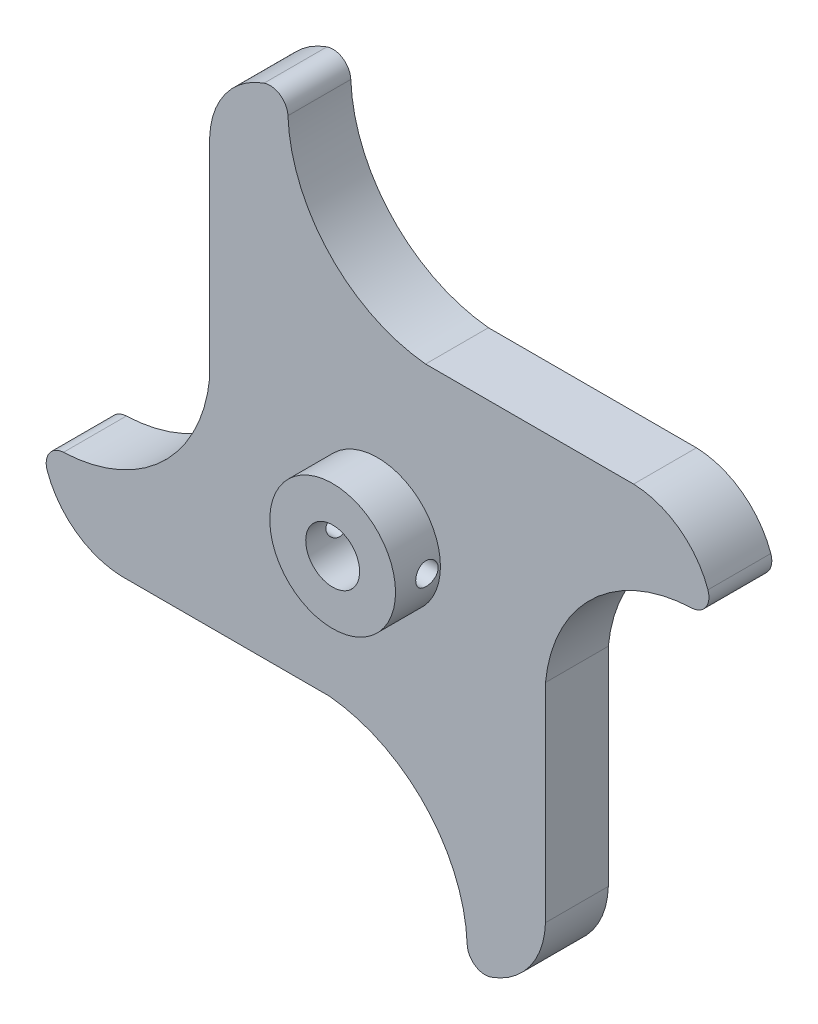
SolidWorks part; units mm, degrees
ref_plane "前视基准面" through (0, 0, 0) normal (0, 0, 1) x (1, 0, 0)
ref_plane "上视基准面" through (0, 0, 0) normal (0, 1, 0) x (1, 0, 0)
ref_plane "右视基准面" through (0, 0, 0) normal (1, 0, 0) x (0, 0, -1)
sketch "草图1" plane through (0, 0, 0) normal (0, 0, 1) x (1, 0, 0)
  circle A0 centre (0, 0) radius 3
  arc A5 (40.8798, 28.7896) -> (28.7896, 40.8798) centre (0, 0) ccw
  arc A7 (-28.7896, 40.8798) -> (-40.8798, 28.7896) centre (0, 0) ccw
  arc A9 (-40.8798, -28.7896) -> (-28.7896, -40.8798) centre (0, 0) ccw
  arc A11 (28.7896, -40.8798) -> (40.8798, -28.7896) centre (0, 0) ccw
  arc A13 (-22.8945, 32.8) -> (22.8945, 32.8) centre (0, 55.6945) ccw
  arc A14 (32.8, 22.8945) -> (32.8, -22.8945) centre (55.6945, 0) ccw
  arc A15 (22.8945, -32.8) -> (-22.8945, -32.8) centre (0, -55.6945) ccw
  arc A16 (-32.8, -22.8945) -> (-32.8, 22.8945) centre (-55.6945, 0) ccw
  arc A21 (-28.7896, 40.8798) -> (28.7896, 40.8798) centre (0, 55.6945) ccw
  arc A22 (40.8798, 28.7896) -> (40.8798, -28.7896) centre (55.6945, 0) ccw
  arc A23 (28.7896, -40.8798) -> (-28.7896, -40.8798) centre (0, -55.6945) ccw
  arc A24 (-40.8798, -28.7896) -> (-40.8798, 28.7896) centre (-55.6945, 0) ccw
  point P13 (45, 0)
  point P16 (0, 0)
  point P45 (0, 0)
  point P47 (0, 0)
  point P63 (0, 0)
  dimension "D3" = 4
  dimension "D4" = 4
extrude "凸台-拉伸1" add sketch "草图1" along normal blind 7 contours A24 A16 A9 A23 A15 A11 A22 A14 A5 A21 A13 A7 A0
sketch "草图2" plane through (0, 0, 7) normal (0, 0, 1) x (1, 0, 0)
  line L0 (24.2343, 0) -> (24.2343, 20.8516)
  line L1 (0, -24.2343) -> (-200, -24.2343)
  line L2 (-200, -71.6) -> (3.2733, -71.6)
  line L3 (0, -70) -> (-200, -70)
  line L4 (-200, -23.4) -> (-200, -71.6)
  line L5 (24.2343, 34.0432) -> (24.2343, 20.8516)
  line L6 (-200, -47.5) -> (-20.9464, -47.5)
  line L7 (-200, -23.4) -> (-42.5285, -23.4)
  line L8 (70, 0) -> (70, 107.3223)
  line L9 (24.2343, 34.0432) -> (24.2343, 107.3223)
  line L10 (-35.8334, -17.6395) -> (24.2343, 34.0432)
  line L11 (24.2343, 34.0432) -> (-43.4982, -24.2343)
  line L12 (0, -24.2343) -> (0, 0)
  line L13 (0, 0) -> (0, -24.2343)
  line L14 (-43.4982, -24.2343) -> (-43.4982, -70)
  line L15 (-310.8913, -229.5208) -> (-198.8913, -229.5208)
  line L16 (-254.8913, -229.5208) -> (-251.3913, -229.5208)
  line L17 (-251.3913, -229.5208) -> (-258.3913, -229.5208)
  line L18 (-258.3913, -229.5208) -> (-258.3913, -112.5315)
  line L19 (-258.3913, -112.5315) -> (-251.3913, -112.5315)
  line L20 (-251.3913, -112.5315) -> (-251.3913, -229.5208)
  line L21 (24.2343, 107.3223) -> (70, 107.3223)
  line L22 (47.1172, 107.3223) -> (47.1172, -141.393)
  line L23 (-20.9464, -47.5) -> (114.3656, -47.5)
  line L24 (0, 0) -> (0, -24.2343)
  circle A0 centre (0, -49) radius 21
  circle A1 centre (-310.8913, -229.5208) radius 38.25
  arc A2 (0, -24.2343) -> (24.2343, 0) centre (0, 0) ccw
  arc A3 (0, -70) -> (70, 0) centre (0, 0) ccw
  circle A4 centre (-198.8913, -229.5208) radius 38.25
  circle A5 centre (0, 0) radius 47.1172
  circle A10 centre (-254.8913, -208.9571) radius 21.4063
  point P19 (0, 0)
sketch "草图5" plane through (0, 0, 7) normal (0, 0, 1) x (1, 0, 0)
  line L1 (0, 2.5) -> (-1.7806, 2.5)
  line L2 (-1.7806, 2.5) -> (1.6583, 2.5)
  arc A0 (1.6583, 2.5) -> (-1.6583, 2.5) centre (0, 0) ccw
  circle A1 centre (0, 0) radius 7
extrude "凸台-拉伸2" add sketch "草图5" along normal blind 4
sketch "草图10" plane through (0, 0, 7) normal (0, 0, -1) x (-1, 0, 0)
  line L0 (-1.6583, 2.5) -> (1.6583, 2.5) construction
  line L1 (-1.6583, 2.5) -> (1.6583, 2.5)
  arc A0 (-1.6583, 2.5) -> (1.6583, 2.5) centre (0, 0) cw
  arc A1 (1.6583, 2.5) -> (-1.6583, 2.5) centre (0, 0) ccw construction
extrude "凸台-拉伸3" add sketch "草图10" along normal up to surface (7 mm away) up to face at (0, 0, 0)
sketch "草图11" plane through (0, 0, 0) normal (1, 0, 0) x (0, 0, -1)
  line L0 (0, 0) -> (-7, 0)
  line L1 (-7, 0) -> (-10, 0)
  circle A0 centre (-8.5, 0) radius 1.25
extrude "切除-拉伸5" cut sketch "草图11" against normal blind 15 and the other way blind 8 contours L1 A0 | L1 A0
sketch "草图12" plane through (0, 0, 11) normal (0, 0, 1) x (1, 0, 0)
  circle A0 centre (0, 0) radius 6
  circle A1 centre (0, 0) radius 3
extrude "凸台-拉伸4" add sketch "草图12" along normal blind 1
sketch "草图13" plane through (0, 0, 0) normal (0, 0, -1) x (-1, 0, 0)
  arc A0 (-25.2436, 31.0284) -> (25.2436, 31.0284) centre (0, 50.6945) ccw
  arc A1 (31.0284, 25.2436) -> (31.0284, -25.2436) centre (50.6945, 0) ccw
  arc A2 (25.2436, -31.0284) -> (-25.2436, -31.0284) centre (0, -50.6945) ccw
  arc A3 (-31.0284, -25.2436) -> (-31.0284, 25.2436) centre (-50.6945, 0) ccw
  arc A4 (-25.2436, 31.0284) -> (-31.0284, 25.2436) centre (0, 0) ccw
  circle A5 centre (0, 0) radius 82.6945
  arc A6 (-31.0284, -25.2436) -> (-25.2436, -31.0284) centre (0, 0) ccw
  arc A7 (25.2436, -31.0284) -> (31.0284, -25.2436) centre (0, 0) ccw
  arc A8 (31.0284, 25.2436) -> (25.2436, 31.0284) centre (0, 0) ccw
  point P14 (0, 0)
  dimension "D1" = 4
extrude "切除-拉伸13" cut sketch "草图13" against normal blind 10
fillet "圆角1" radius 2 4 edges at (-31.0284, -25.2436, 3.5) (31.0284, -25.2436, 3.5) (25.2436, 31.0284, 3.5) (-31.0284, 25.2436, 3.5)
fillet "圆角2" radius 2 4 edges at (-25.2436, -31.0284, 3.5) (25.2436, -31.0284, 3.5) (31.0284, 25.2436, 3.5) (-25.2436, 31.0284, 3.5)
sketch "草图14" plane through (0, 0, 0) normal (0, 0, -1) x (-1, 0, 0)
  line L0 (0, 18.6945) -> (-34.0956, 18.6945)
  line L1 (18.6945, 0) -> (18.6945, 34.0956)
  line L2 (0, -18.6945) -> (34.0956, -18.6945)
  line L3 (-18.6945, 0) -> (-18.6945, -34.0956)
  line L4 (34.0956, -16.9082) -> (34.0956, -18.6945)
  line L5 (-16.9082, -34.0956) -> (-18.6945, -34.0956)
  line L6 (-34.0956, 16.9082) -> (-34.0956, 18.6945)
  line L7 (16.9082, 34.0956) -> (18.6945, 34.0956)
  line L8 (13.8017, 34.0956) -> (18.6945, 34.0956)
  line L9 (34.0956, -13.8017) -> (34.0956, -18.6945)
  line L10 (-13.8017, -34.0956) -> (-18.6945, -34.0956)
  line L11 (-34.0956, 13.8017) -> (-34.0956, 18.6945)
  arc A1 (-23.9852, 29.5117) -> (23.9852, 29.5117) centre (0, 50.6945) ccw construction
  arc A5 (0, 18.6945) -> (13.8017, 34.0956) centre (-0.7997, 33.296) ccw
  arc A6 (18.6945, 0) -> (34.0956, -13.8017) centre (33.296, 0.7997) ccw
  arc A7 (0, -18.6945) -> (-13.8017, -34.0956) centre (0.7997, -33.296) ccw
  arc A8 (-18.6945, 0) -> (-34.0956, 13.8017) centre (-33.296, -0.7997) ccw
  point P22 (0, 0)
  point P29 (0, 0)
  point P35 (0, 0)
  point P41 (0, 0)
  arc M1 (-23.9852, -29.5117) -> (23.9852, -29.5117) centre (0, -50.6945) cw
  arc M5 (29.5117, -23.9852) -> (29.5117, 23.9852) centre (50.6945, 0) cw
  arc M9 (23.9852, 29.5117) -> (-23.9852, 29.5117) centre (0, 50.6945) cw
  arc M13 (-29.5117, 23.9852) -> (-29.5117, -23.9852) centre (-50.6945, 0) cw
  arc M17 (1.6583, 2.5) -> (-1.6583, 2.5) centre (0, 0) cw
  line M18 (-1.6583, 2.5) -> (1.6583, 2.5)
  dimension "D1" = 4
  dimension "D3" = 4
  dimension "D2" = 4
  dimension "D4" = 4
extrude "凸台-拉伸5" add sketch "草图14" against normal up to surface (7 mm away) contours L3 L2 L1 L0 M13 M1 M5 M9 M18 M17 | A8 L0 L6 L11 M13 | A5 L1 L7 L8 M9 | A6 L2 L4 L9 M5 | A7 L3 L5 L10 M1 up to face at (0, 0, 7)
sketch "草图15" plane through (0, 0, 0) normal (0, 0, -1) x (-1, 0, 0)
  line L0 (-24.7231, 18.6945) -> (0, 18.6945)
  line L1 (18.6945, 0) -> (18.6945, 24.7231)
  line L2 (24.7231, -18.6945) -> (0.9271, -18.708)
  line L3 (24.7231, -18.6945) -> (0, -18.6945)
  line L4 (18.6945, 24.7231) -> (18.6945, 0)
  line L5 (24.7231, -18.6945) -> (0, -18.6945)
  line L6 (-18.6945, -24.7231) -> (-18.6945, 0)
  line L7 (-18.6945, -24.7231) -> (-25.6921, -33.3347)
  line L8 (-25.6921, -33.3347) -> (-42.4976, -12.5302)
  line L9 (-42.4976, -12.5302) -> (-18.6945, 0)
  line L10 (-12.5302, 42.4976) -> (0, 18.6945)
  line L11 (-33.3347, 25.6921) -> (-12.5302, 42.4976)
  line L12 (-24.7231, 18.6945) -> (-33.3347, 25.6921)
  line L13 (42.4976, 12.5302) -> (18.6945, 0)
  line L14 (25.6921, 33.3347) -> (42.4976, 12.5302)
  line L15 (18.6945, 24.7231) -> (25.6921, 33.3347)
  line L16 (12.5302, -42.4976) -> (0, -18.6945)
  line L17 (33.3347, -25.6921) -> (12.5302, -42.4976)
  line L18 (24.7231, -18.6945) -> (33.3347, -25.6921)
  arc A0 (-23.9852, 29.5117) -> (0, 18.6945) centre (0, 50.6945) ccw construction
  arc A1 (0, 18.6945) -> (13.8017, 34.0956) centre (-0.7997, 33.296) ccw construction
  arc A2 (18.6945, 24.7231) -> (23.9852, 29.5117) centre (0, 50.6945) ccw construction
  arc A3 (23.9852, -29.5117) -> (0, -18.6945) centre (0, -50.6945) ccw construction
  point P35 (0, 0)
  point P47 (0, 0)
  arc M1 (-23.9852, -29.5117) -> (-18.6945, -24.7231) centre (0, -50.6945) cw
  arc M5 (0, -18.6945) -> (23.9852, -29.5117) centre (0, -50.6945) cw
  arc M6 (23.9852, -29.5117) -> (26.8255, -29.6714) centre (25.4843, -28.1878) ccw
  arc M7 (26.8255, -29.6714) -> (29.6714, -26.8255) centre (0, 0) ccw
  arc M8 (29.6714, -26.8255) -> (29.5117, -23.9852) centre (28.1878, -25.4843) ccw
  arc M9 (29.5117, -23.9852) -> (24.7231, -18.6945) centre (50.6945, 0) cw
  arc M13 (18.6945, 0) -> (29.5117, 23.9852) centre (50.6945, 0) cw
  arc M14 (29.5117, 23.9852) -> (29.6714, 26.8255) centre (28.1878, 25.4843) ccw
  arc M15 (29.6714, 26.8255) -> (26.8255, 29.6714) centre (0, 0) ccw
  arc M16 (26.8255, 29.6714) -> (23.9852, 29.5117) centre (25.4843, 28.1878) ccw
  arc M17 (23.9852, 29.5117) -> (18.6945, 24.7231) centre (0, 50.6945) cw
  arc M21 (0, 18.6945) -> (-23.9852, 29.5117) centre (0, 50.6945) cw
  arc M22 (-23.9852, 29.5117) -> (-26.8255, 29.6714) centre (-25.4843, 28.1878) ccw
  arc M23 (-26.8255, 29.6714) -> (-29.6714, 26.8255) centre (0, 0) ccw
  arc M24 (-29.6714, 26.8255) -> (-29.5117, 23.9852) centre (-28.1878, 25.4843) ccw
  arc M25 (-29.5117, 23.9852) -> (-24.7231, 18.6945) centre (-50.6945, 0) cw
  arc M29 (-18.6945, 0) -> (-29.5117, -23.9852) centre (-50.6945, 0) cw
  arc M30 (-29.5117, -23.9852) -> (-29.6714, -26.8255) centre (-28.1878, -25.4843) ccw
  arc M31 (-29.6714, -26.8255) -> (-26.8255, -29.6714) centre (0, 0) ccw
  arc M32 (-26.8255, -29.6714) -> (-23.9852, -29.5117) centre (-25.4843, -28.1878) ccw
  dimension "D1" = 4
  dimension "D2" = 4
extrude "切除-拉伸14" cut sketch "草图15" against normal blind 10 contours L12 L10 L11 M25 M24 M23 M22 M21 | L0 M25 M21 M22 M23 M24 | L1 M13 M14 M15 M16 M17 | L15 L13 L14 M17 M16 M15 M14 M13 | L2 M9 M5 M6 M7 M8 | L18 L16 L17 M9 M8 M7 M6 M5 | L9 L8 L7 M1 M32 M31 M30 M29 | L6 M1 M29 M30 M31 M32
fillet "圆角3" radius 3 4 edges at (34.0956, 18.6945, 3.5) (18.6945, -34.0956, 3.5) (-34.0956, -18.6945, 3.5) (-18.6945, 34.0956, 3.5)
fillet "圆角4" radius 1 4 edges at (-34.0956, -13.8017, 3.5) (13.8017, -34.0956, 3.5) (34.0956, 13.8017, 3.5) (-13.8017, 34.0956, 3.5)
sketch "草图16" plane through (0, 0, 0) normal (0, 0, -1) x (-1, 0, 0)
  arc A0 (5.3467, -18.6945) -> (-9.9109, -37.2905) centre (7.0159, -35.6213) ccw
  arc A1 (-18.6945, -27.9842) -> (-9.9109, -37.2905) centre (-9.6496, -28.2455) ccw
  arc A2 (-18.6945, -5.3467) -> (-37.2905, 9.9109) centre (-35.6213, -7.0159) ccw
  arc A3 (-27.9842, 18.6945) -> (-37.2905, 9.9109) centre (-28.2455, 9.6496) ccw
  arc A4 (-5.3467, 18.6945) -> (9.9109, 37.2905) centre (-7.0159, 35.6213) ccw
  arc A5 (27.9842, -18.6945) -> (37.2905, -9.9109) centre (28.2455, -9.6496) ccw
  arc A6 (18.6945, 27.9842) -> (9.9109, 37.2905) centre (9.6496, 28.2455) ccw
  arc A9 (18.6945, 5.3467) -> (37.2905, -9.9109) centre (35.6213, 7.0159) ccw
  point P21 (0, 0)
  line M3 (34.0956, -15.6945) -> (34.0956, -14.8223)
  arc M4 (34.0956, -14.8223) -> (33.1085, -13.8224) centre (33.0956, -14.8223) ccw
  arc M5 (33.1085, -13.8224) -> (18.6945, 0) centre (33.296, 0.7997) cw
  line M6 (18.6945, 0) -> (18.6945, 31.0956)
  arc M7 (18.6945, 31.0956) -> (15.6945, 34.0956) centre (15.6945, 31.0956) ccw
  line M8 (15.6945, 34.0956) -> (14.8223, 34.0956)
  arc M9 (14.8223, 34.0956) -> (13.8224, 33.1085) centre (14.8223, 33.0956) ccw
  arc M10 (13.8224, 33.1085) -> (0, 18.6945) centre (-0.7997, 33.296) cw
  line M11 (0, 18.6945) -> (-31.0956, 18.6945)
  arc M12 (-31.0956, 18.6945) -> (-34.0956, 15.6945) centre (-31.0956, 15.6945) ccw
  line M13 (-34.0956, 15.6945) -> (-34.0956, 14.8223)
  arc M14 (-34.0956, 14.8223) -> (-33.1085, 13.8224) centre (-33.0956, 14.8223) ccw
  arc M15 (-33.1085, 13.8224) -> (-18.6945, 0) centre (-33.296, -0.7997) cw
  line M16 (-18.6945, 0) -> (-18.6945, -31.0956)
  arc M17 (-18.6945, -31.0956) -> (-15.6945, -34.0956) centre (-15.6945, -31.0956) ccw
  line M18 (-15.6945, -34.0956) -> (-14.8223, -34.0956)
  arc M19 (-14.8223, -34.0956) -> (-13.8224, -33.1085) centre (-14.8223, -33.0956) ccw
  arc M20 (-13.8224, -33.1085) -> (0, -18.6945) centre (0.7997, -33.296) cw
  arc M21 (0, -18.6945) -> (0.9271, -18.708) centre (0, -50.6945) cw
  line M22 (0.9271, -18.708) -> (24.7231, -18.6945)
  arc M24 (31.0956, -18.6945) -> (34.0956, -15.6945) centre (31.0956, -15.6945) ccw
  dimension "D1" = 4
sketch "草图17" plane through (0, 0, 7) normal (0, 0, 1) x (1, 0, 0)
  arc A0 (-18.6945, 27.9842) -> (-9.9109, 37.2905) centre (-9.6496, 28.2455) cw
  arc A1 (-9.9109, 37.2905) -> (5.3467, 18.6945) centre (7.0159, 35.6213) ccw
  arc A2 (37.2905, 9.9109) -> (18.6945, -5.3467) centre (35.6213, -7.0159) ccw
  arc A3 (27.9842, 18.6945) -> (37.2905, 9.9109) centre (28.2455, 9.6496) cw
  arc A4 (9.9109, -37.2905) -> (-5.3467, -18.6945) centre (-7.0159, -35.6213) ccw
  arc A5 (18.6945, -27.9842) -> (9.9109, -37.2905) centre (9.6496, -28.2455) cw
  arc A6 (-37.2905, -9.9109) -> (-18.6945, 5.3467) centre (-35.6213, 7.0159) ccw
  arc A7 (-27.9842, -18.6945) -> (-37.2905, -9.9109) centre (-28.2455, -9.6496) cw
  point P26 (0, 0)
  dimension "D1" = 4
extrude "凸台-拉伸6" add sketch "草图16" against normal up to surface (7 mm away) contours A6 A4 M7 M11 M10 M9 M8 | A3 A2 M12 M16 M15 M14 M13 | A1 A0 M17 M22 M21 M20 M19 M18 | A9 A5 M6 M5 M4 M3 M24 up to face at (-1.1659, -1.7, 7)
sketch "草图18" plane through (0, 0, 7) normal (0, 0, 1) x (1, 0, 0)
  line L0 (5.3467, 18.6945) -> (27.9842, 18.6945)
  line L1 (18.6945, -5.3467) -> (18.6945, -27.9842)
  line L2 (-5.3467, -18.6945) -> (-27.9842, -18.6945)
  line L3 (-18.6945, 5.3467) -> (-18.6945, 27.9842)
  arc A0 (-18.6945, 27.9842) -> (-9.9109, 37.2905) centre (-9.6496, 28.2455) cw
  arc A1 (-9.9109, 37.2905) -> (5.3467, 18.6945) centre (7.0159, 35.6213) ccw
  arc A2 (27.9842, 18.6945) -> (37.2905, 9.9109) centre (28.2455, 9.6496) cw
  arc A3 (37.2905, 9.9109) -> (18.6945, -5.3467) centre (35.6213, -7.0159) ccw
  arc A4 (18.6945, -27.9842) -> (9.9109, -37.2905) centre (9.6496, -28.2455) cw
  arc A5 (9.9109, -37.2905) -> (-5.3467, -18.6945) centre (-7.0159, -35.6213) ccw
  arc A6 (-27.9842, -18.6945) -> (-37.2905, -9.9109) centre (-28.2455, -9.6496) cw
  arc A7 (-37.2905, -9.9109) -> (-18.6945, 5.3467) centre (-35.6213, 7.0159) ccw
  circle A8 centre (0, 0) radius 47.2388
  point P31 (0, 0)
  dimension "D1" = 4
extrude "切除-拉伸15" cut sketch "草图18" against normal blind 10
fillet "圆角5" radius 2 4 edges at (-37.2905, -9.9109, 3.5) (9.9109, -37.2905, 3.5) (37.2905, 9.9109, 3.5) (-9.9109, 37.2905, 3.5)
sketch "草图19" plane through (0, 0, 7) normal (0, 0, 1) x (1, 0, 0)
  circle A0 centre (0, 0) radius 9.5
  circle A1 centre (9.5, 0) radius 3
extrude "切除-拉伸16" [suppressed] cut sketch "草图19" against normal blind 10 contours A0 A1 | A0 A1
sketch "草图22" plane through (0, 0, 11) normal (0, 0, 1) x (1, 0, 0)
  circle A0 centre (0, 0) radius 6
  circle A1 centre (0, 0) radius 7
extrude "凸台-拉伸8" add sketch "草图22" along normal up to surface (1 mm away) up to face at (6, 0, 12)
